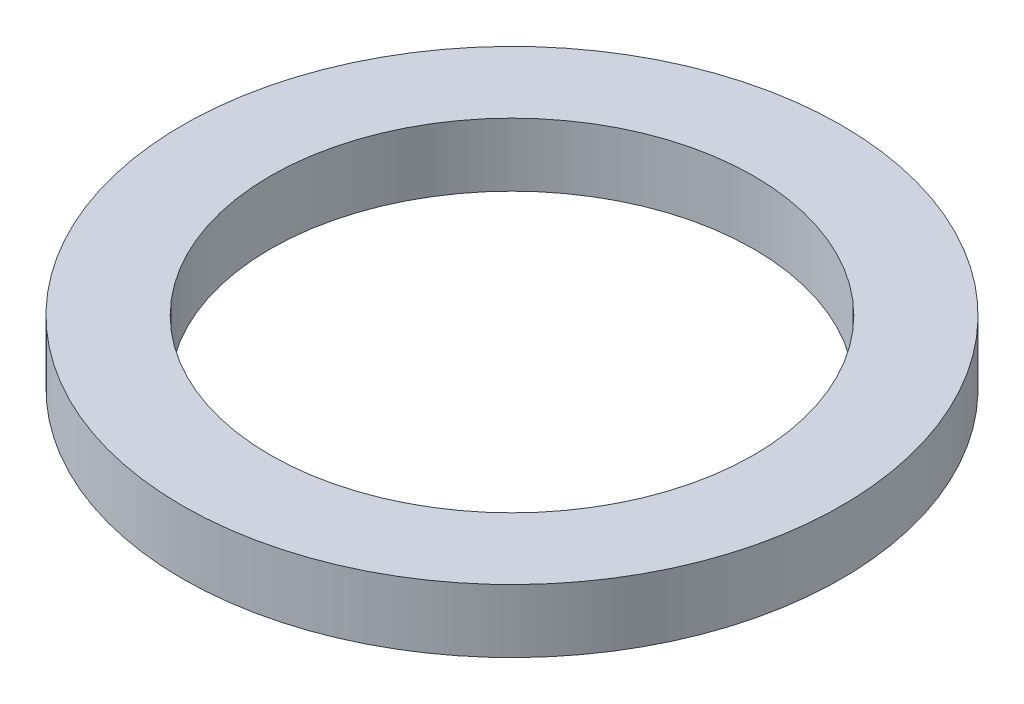
SolidWorks part; units mm, degrees
material "1023 Karbon Çeliği Levha (SS)"
ref_plane "Ön Düzlem" through (0, 0, 0) normal (0, 0, 1) x (1, 0, 0)
ref_plane "Üst Düzlem" through (0, 0, 0) normal (0, 1, 0) x (1, 0, 0)
ref_plane "Sağ Düzlem" through (0, 0, 0) normal (1, 0, 0) x (0, 0, -1)
sketch "Çizim1" plane through (0, 0, 0) normal (0, 1, 0) x (1, 0, 0)
  circle A0 centre (0, 0) radius 10.84
extrude "Yükseklik-Ekstrüzyon1" add sketch "Çizim1" along normal blind 2.08
sketch "Çizim2" plane through (0, 2.08, 0) normal (0, 1, 0) x (1, 0, 0)
  circle A0 centre (0, 0) radius 7.95
extrude "Kes-Ekstrüzyon1" cut sketch "Çizim2" against normal blind 3.08 and the other way blind 2
